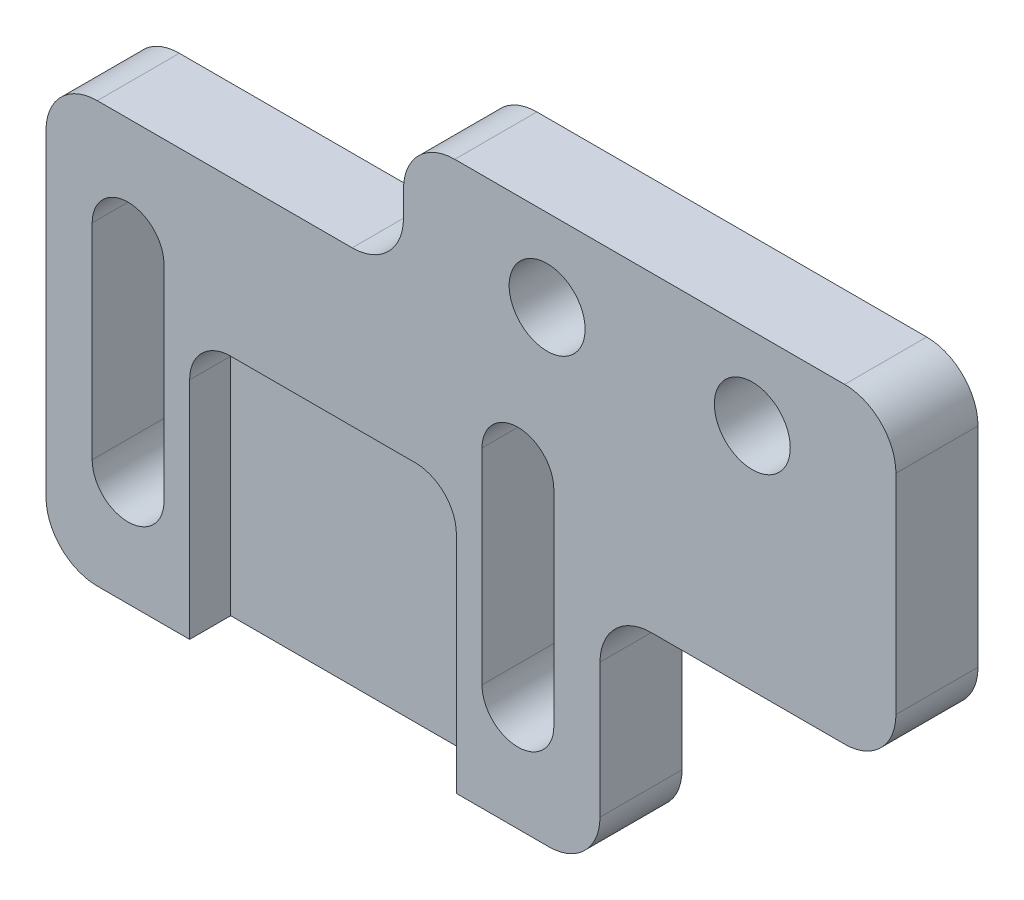
SolidWorks part; units mm, degrees
ref_plane "Front Plane" through (0, 0, 0) normal (0, 0, 1) x (1, 0, 0)
ref_plane "Top Plane" through (0, 0, 0) normal (0, 1, 0) x (1, 0, 0)
ref_plane "Right Plane" through (0, 0, 0) normal (1, 0, 0) x (0, 0, -1)
sketch "Sketch1" plane through (0, 0, 0) normal (0, 0, 1) x (1, 0, 0)
  line L0 (-6.4229, 8.4541) -> (-6.4229, -1.5459) construction
  line L1 (-12, 19.9744) -> (12, 19.9744)
  line L2 (-12, 19.9744) -> (-12, 13.7385)
  line L3 (-2.4229, 4.7879) -> (12, 4.7879)
  line L4 (12, 19.9744) -> (12, 4.7879)
  line L5 (-29.4229, -6.7521) -> (-2.4229, -6.7521)
  line L6 (-29.4229, -6.7521) -> (-29.4229, 13.7385)
  line L7 (-29.4229, 13.7385) -> (-12, 13.7385)
  line L8 (-2.4229, -6.7521) -> (-2.4229, 4.7879)
  line L9 (-4.6729, 8.4541) -> (-4.6729, -1.5459)
  line L10 (-8.1729, 8.4541) -> (-8.1729, -1.5459)
  line L11 (-25.4229, 8.4541) -> (-25.4229, -1.5459) construction
  line L12 (-23.6729, 8.4541) -> (-23.6729, -1.5459)
  line L13 (-27.1729, 8.4541) -> (-27.1729, -1.5459)
  circle A0 centre (-5, 15.9744) radius 1.85
  circle A1 centre (5, 15.9744) radius 1.85
  arc A2 (-4.6729, 8.4541) -> (-8.1729, 8.4541) centre (-6.4229, 8.4541) ccw
  arc A3 (-8.1729, -1.5459) -> (-4.6729, -1.5459) centre (-6.4229, -1.5459) ccw
  arc A4 (-23.6729, 8.4541) -> (-27.1729, 8.4541) centre (-25.4229, 8.4541) ccw
  arc A5 (-27.1729, -1.5459) -> (-23.6729, -1.5459) centre (-25.4229, -1.5459) ccw
  point P9 (0, 19.9744)
  point P14 (-6.4229, 3.4541)
  point P17 (-25.4229, -1.3905)
  point P21 (0, 0)
  point P22 (-25.4229, 3.4541)
  point P25 (-29.4229, 12.4541)
  point P30 (0, 0)
  point P31 (0, 0)
  dimension "D6" = 3.7
  dimension "D7" = 27
  dimension "D3" = 10
  dimension "D4" = 4
  dimension "D5" = 5
  dimension "D8" = 4
  dimension "D9" = 10
  dimension "D12" = 24
extrude "Boss-Extrude1" add sketch "Sketch1" along normal blind 4
fillet "Fillet1" radius 2.5 8 edges at (12, 4.7879, 2) (-2.4229, -6.7521, 2) (-2.4229, 4.7879, 2) (12, 19.9744, 2) (-12, 19.9744, 2) (-12, 13.7385, 2) (-29.4229, 13.7385, 2) (-29.4229, -6.7521, 2)
sketch "Sketch2" plane through (0, 0, 4) normal (0, 0, 1) x (1, 0, 0)
  line L1 (-22.4229, 6.2041) -> (-9.4229, 6.2041)
  line L2 (-22.4229, 6.2041) -> (-22.4229, -13.7959)
  line L3 (-22.4229, -13.7959) -> (-9.4229, -13.7959)
  line L4 (-9.4229, 6.2041) -> (-9.4229, -13.7959)
  line L8 (-29.4229, 11.2385) -> (-29.4229, -4.2521) construction
  line L9 (-2.4229, -4.2521) -> (-2.4229, 2.2879) construction
  dimension "D1" = 7
  dimension "D2" = 7
  dimension "D3" = 20
extrude "Cut-Extrude1" cut sketch "Sketch2" against normal blind 2 contours L4 L3 L2 L1
fillet "Fillet2" radius 2 2 edges at (-9.4229, 6.2041, 3) (-22.4229, 6.2041, 3)
